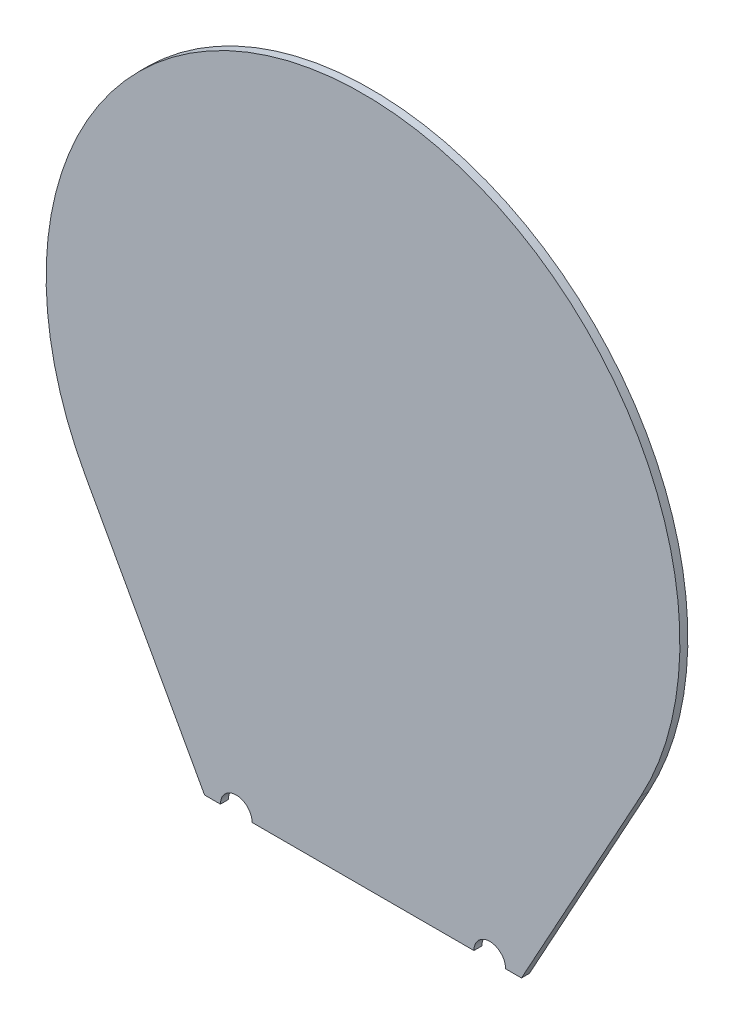
SolidWorks part; units mm, degrees
ref_plane "Plano frontal" through (0, 0, 0) normal (0, 0, 1) x (1, 0, 0)
ref_plane "Plano superior" through (0, 0, 0) normal (0, 1, 0) x (1, 0, 0)
ref_plane "Plano direito" through (0, 0, 0) normal (1, 0, 0) x (0, 0, -1)
sketch "Sketch1" plane through (0, 0, 0) normal (0, 0, 1) x (1, 0, 0)
  line L0 (-15, -35) -> (-7.5, -35)
  line L1 (-15, -35) -> (15, -35)
  line L4 (-15, -35) -> (-7.5, -35)
  line L7 (15, -35) -> (26.2929, -14.4459)
  line L16 (-15, -35) -> (-26.2929, -14.4459)
  arc A2 (26.2929, -14.4459) -> (-26.2929, -14.4459) centre (0, 0) ccw
  point P10 (0, -35)
  dimension "D3" = 60
  dimension "D5" = 30
  dimension "D6" = 7.5
extrude "Boss-Extrude1" add sketch "Sketch1" along normal blind 0.7544
sketch "Esboço1" plane through (0, 0, 0.7544) normal (0, 0, 1) x (1, 0, 0)
  line L0 (-15, -35) -> (-12, -35)
  line L1 (-15, -35) -> (15, -35) construction
  line L2 (0, -35) -> (0, -31.223)
  circle A0 centre (-12, -35) radius 1.5
  circle A1 centre (12, -35) radius 1.5
  line M7 (-15, -35) -> (15, -35)
  dimension "D2" = 3
  dimension "D1" = 3
extrude "Corte-extrusão1" cut sketch "Esboço1" against normal blind 10 contours A1 M7 | A0 L0 M7
